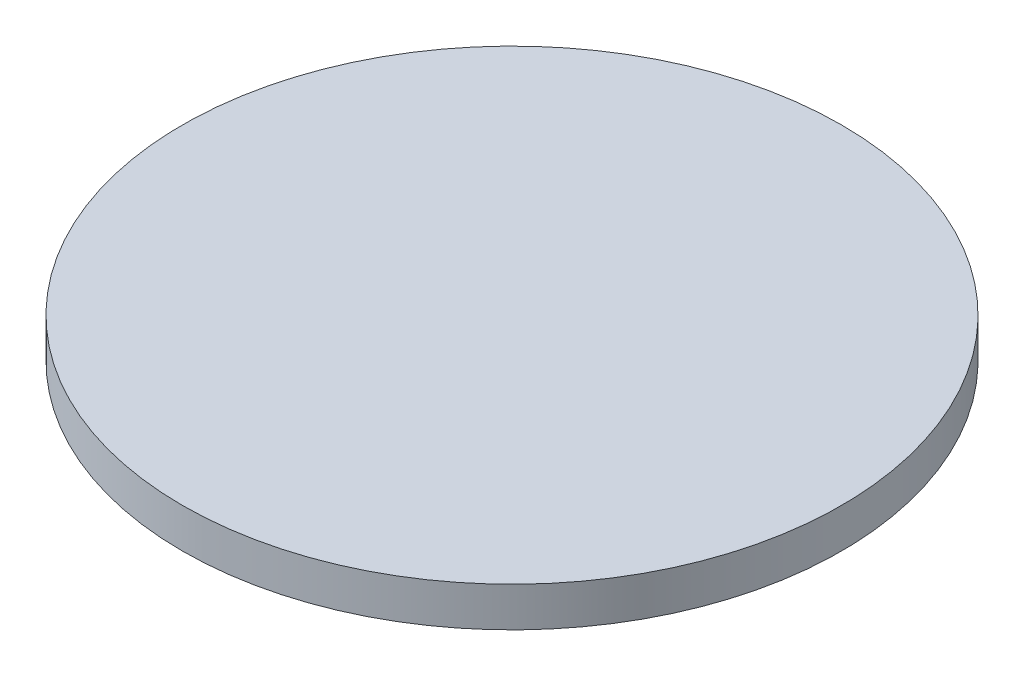
SolidWorks part; units mm, degrees
ref_plane "Piano frontale" through (0, 0, 0) normal (0, 0, 1) x (1, 0, 0)
ref_plane "Piano superiore" through (0, 0, 0) normal (0, 1, 0) x (1, 0, 0)
ref_plane "Piano destro" through (0, 0, 0) normal (1, 0, 0) x (0, 0, -1)
sketch "Schizzo1" plane through (0, 0, 0) normal (0, 1, 0) x (1, 0, 0)
  circle A0 centre (0, 0) radius 50
  dimension "D1" = 100
extrude "Estrusione-Estrusione1" add sketch "Schizzo1" along normal blind 6 contours A0
sketch "Schizzo2" plane through (0, 0, 0) normal (0, -1, 0) x (1, 0, 0)
  line L0 (-12.5, 12) -> (12.5, -12) construction
  line L1 (12.5, -12) -> (-12.5, -12)
  line L2 (12.5, -12) -> (12.5, 12)
  line L3 (12.5, 12) -> (-12.5, 12)
  line L4 (-12.5, -12) -> (-12.5, 12)
  line L5 (12.5, 12) -> (-12.5, -12) construction
  circle A2 centre (0, 0) radius 35
  point P8 (0, 0)
  dimension "D3" = 70
  dimension "D1" = 25
  dimension "D2" = 24
